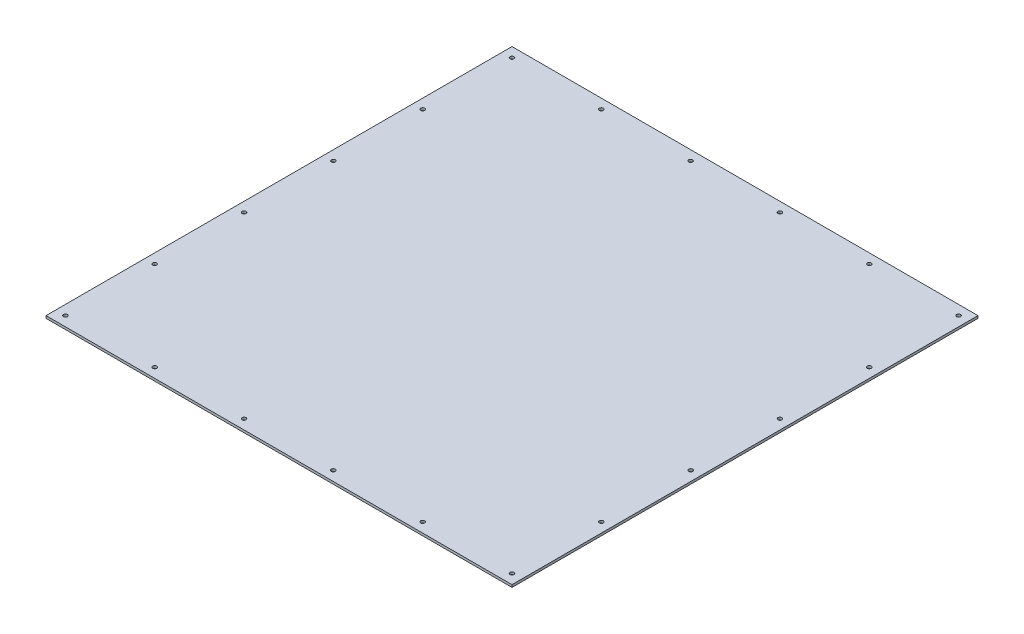
SolidWorks part; units mm, degrees
ref_plane "Front Plane" through (0, 0, 0) normal (0, 0, 1) x (1, 0, 0)
ref_plane "Top Plane" through (0, 0, 0) normal (0, 1, 0) x (1, 0, 0)
ref_plane "Right Plane" through (0, 0, 0) normal (1, 0, 0) x (0, 0, -1)
sketch "Sketch1" plane through (0, 0, 0) normal (0, 1, 0) x (1, 0, 0)
  line L1 (-304.8, -304.8) -> (304.8, -304.8)
  line L2 (-304.8, -304.8) -> (-304.8, 304.8)
  line L3 (-304.8, 304.8) -> (304.8, 304.8)
  line L4 (304.8, -304.8) -> (304.8, 304.8)
  line L5 (-304.8, -304.8) -> (304.8, 304.8) construction
  line L6 (-304.8, 304.8) -> (304.8, -304.8) construction
  point P0 (0, 0)
  dimension "D1" = 609.6
  dimension "D2" = 609.6
extrude "Boss-Extrude1" add sketch "Sketch1" along normal blind 3.175
sketch "Sketch2" plane through (0, 3.175, 0) normal (0, 1, 0) x (1, 0, 0)
  line L0 (215.9, 292.1) -> (215.9, -292.1) construction
  line L8 (292.1, -292.1) -> (292.1, 292.1)
  line L9 (292.1, 292.1) -> (-292.1, 292.1)
  line L10 (-292.1, 292.1) -> (-292.1, -292.1)
  line L11 (-292.1, -292.1) -> (292.1, -292.1)
  line L12 (292.1, -292.1) -> (292.1, 292.1) construction
  line L13 (292.1, 292.1) -> (-292.1, 292.1) construction
  line L14 (-292.1, 292.1) -> (-292.1, -292.1) construction
  line L15 (-292.1, -292.1) -> (292.1, -292.1) construction
  dimension "D2" = 76.2
  dimension "D1" = 12.7
hole_wizard "#6 (0.204) Diameter Hole1" positions "Sketch3" profile "Sketch4" hole size "#6" standard "ANSI Inch" end condition through all
sketch "Sketch3" plane through (0, 3.175, 0) normal (0, 1, 0) x (1, 0, 0)
  line L0 (-292.1, 292.1) -> (-175.26, 292.1) construction
  line L1 (-175.26, 292.1) -> (-58.42, 292.1) construction
  line L2 (-58.42, 292.1) -> (58.42, 292.1) construction
  line L3 (58.42, 292.1) -> (175.26, 292.1) construction
  line L4 (175.26, 292.1) -> (292.1, 292.1) construction
  line L6 (-292.1, 292.1) -> (-292.1, 175.26) construction
  line L7 (-292.1, 175.26) -> (-292.1, 58.42) construction
  line L8 (-292.1, 58.42) -> (-292.1, -58.42) construction
  line L9 (-292.1, -58.42) -> (-292.1, -175.26) construction
  line L10 (-292.1, -175.26) -> (-292.1, -292.1) construction
  line L13 (0, 0) -> (-292.1, 0) construction
  line L15 (0, 0) -> (0, 292.1) construction
  point P0 (-292.1, 292.1)
  point P3 (-175.26, 292.1)
  point P5 (-58.42, 292.1)
  point P7 (58.42, 292.1)
  point P9 (175.26, 292.1)
  point P33 (-292.1, 175.26)
  point P35 (-292.1, 58.42)
  point P37 (-292.1, -58.42)
  point P39 (-292.1, -175.26)
  point P65 (175.26, -292.1)
  point P66 (58.42, -292.1)
  point P67 (-58.42, -292.1)
  point P68 (-175.26, -292.1)
  point P69 (-292.1, -292.1)
  point P74 (0, 0)
  point P75 (292.1, -292.1)
  point P76 (292.1, -175.26)
  point P77 (292.1, -58.42)
  point P78 (292.1, 58.42)
  point P79 (292.1, 175.26)
  point P80 (292.1, 292.1)
  point P81 (-342.9, 292.1)
sketch "Sketch4" plane through (-292.1, 3.175, -292.1) normal (1, 0, 0) x (0, 0, 1)
  line L0 (0, 0) -> (0, 3.175)
  line L1 (0, 3.175) -> (2.5908, 3.175)
  line L2 (2.5908, 3.175) -> (2.5908, 0)
  line L5 (2.5908, 0) -> (0, 0)
  line L11 (0, -6.35) -> (0, 107.95) construction
  dimension "Thru Hole Dia." = 5.1816
  dimension "Thru Hole Depth" = 3.175
